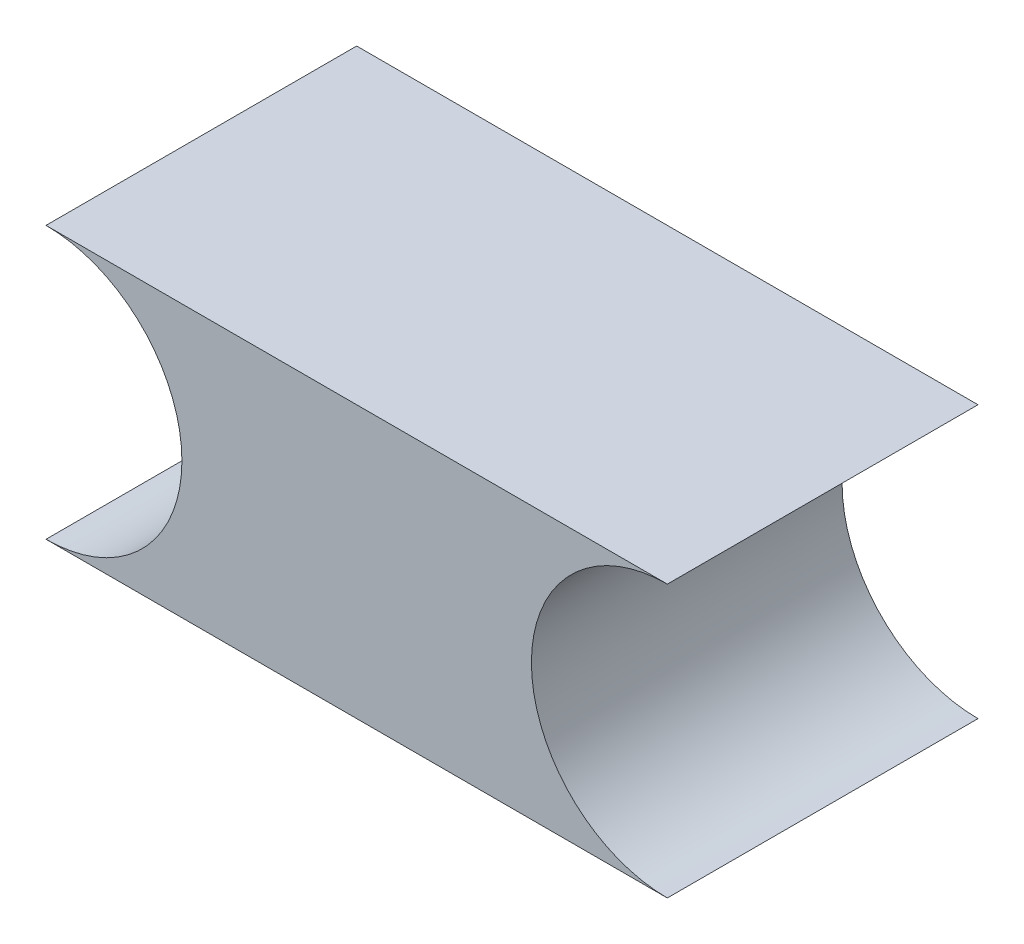
SolidWorks part; units mm, degrees
ref_plane "前视基准面" through (0, 0, 0) normal (0, 0, 1) x (1, 0, 0)
ref_plane "上视基准面" through (0, 0, 0) normal (0, 1, 0) x (1, 0, 0)
ref_plane "右视基准面" through (0, 0, 0) normal (1, 0, 0) x (0, 0, -1)
sketch "草图1" plane through (0, 0, 0) normal (0, 0, 1) x (1, 0, 0)
  line L1 (-31.4852, 28.8243) -> (128.5148, 28.8243)
  line L3 (-31.4852, -41.1757) -> (128.5148, -41.1757)
  arc A0 (-31.4852, -41.1757) -> (-31.4852, 28.8243) centre (-31.4852, -6.1757) ccw
  arc A1 (128.5148, 28.8243) -> (128.5148, -41.1757) centre (128.5148, -6.1757) ccw
extrude "凸台-拉伸1" add sketch "草图1" along normal blind 80
